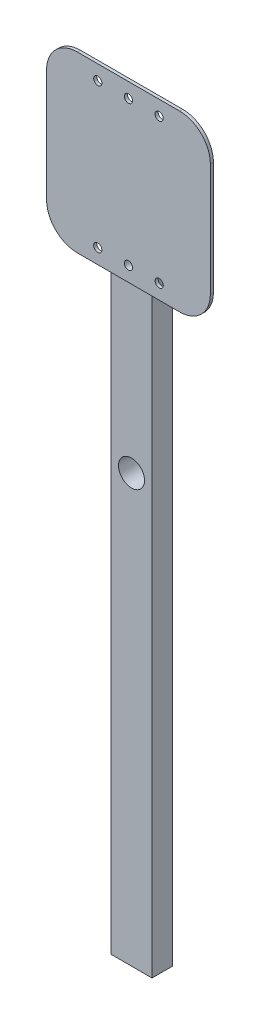
SolidWorks part; units mm, degrees
ref_plane "Alzado" through (0, 0, 0) normal (0, 0, 1) x (1, 0, 0)
ref_plane "Planta" through (0, 0, 0) normal (0, 1, 0) x (1, 0, 0)
ref_plane "Vista lateral" through (0, 0, 0) normal (1, 0, 0) x (0, 0, -1)
sketch "Croquis1" plane through (0, 0, 0) normal (0, 0, 1) x (1, 0, 0)
  line L0 (-50, 85) -> (50, 85)
  line L6 (80, 55) -> (80, -55)
  line L7 (50, -85) -> (-50, -85)
  line L8 (-80, 55) -> (-80, -55)
  arc A0 (-80, -55) -> (-50, -85) centre (-50, -55) ccw
  arc A1 (50, -85) -> (80, -55) centre (50, -55) ccw
  circle A2 centre (0, 70.6) radius 4
  circle A3 centre (0, -70.6) radius 4
  circle A4 centre (-30, 70.6) radius 4
  circle A5 centre (30, 70.6) radius 4
  circle A6 centre (-30, -70.6) radius 4
  circle A7 centre (30, -70.6) radius 4
  arc A8 (80, 55) -> (50, 85) centre (50, 55) ccw
  arc A10 (-80, 55) -> (-50, 85) centre (-50, 55) cw
  point P5 (0, 0)
extrude "Saliente-Extruir1" add sketch "Croquis1" along normal blind 3
sketch "Croquis2" plane through (0, 0, 0) normal (0, 0, 1) x (1, 0, 0)
  line L0 (-20, -665) -> (20, -665)
  line L1 (-20, 0) -> (20, 0)
  line L3 (-20, 0) -> (-20, -665)
  line L5 (20, 0) -> (20, -665)
  circle A0 centre (0, -247.75) radius 12.7
extrude "Saliente-Extruir2" add sketch "Croquis2" against normal blind 20
sketch "Croquis3" plane through (0, 0, 0) normal (0, 0, 1) x (1, 0, 0)
  circle A0 centre (0, -70.6) radius 4
extrude "Cortar-Extruir1" cut sketch "Croquis3" against normal blind 71 and the other way blind 99
